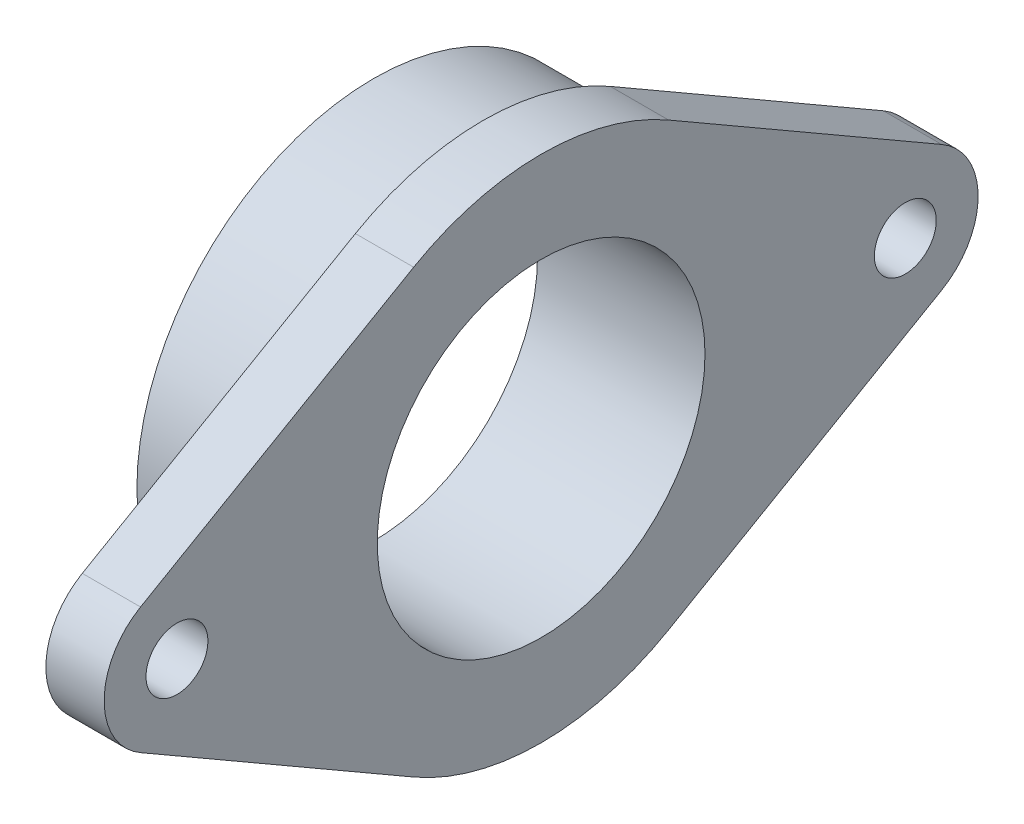
SolidWorks part; units mm, degrees
ref_plane "Front Plane" through (0, 0, 0) normal (0, 0, 1) x (1, 0, 0)
ref_plane "Top Plane" through (0, 0, 0) normal (0, 1, 0) x (1, 0, 0)
ref_plane "Right Plane" through (0, 0, 0) normal (1, 0, 0) x (0, 0, -1)
sketch "Sketch1" plane through (0, 0, 0) normal (1, 0, 0) x (0, 0, -1)
  circle A0 centre (0, 0) radius 32.5
  circle A1 centre (0, 0) radius 22.5
  dimension "D1" = 65
  dimension "D2" = 45
extrude "Boss-Extrude1" add sketch "Sketch1" along normal blind 15
sketch "Sketch2" plane through (15, 0, 0) normal (1, 0, 0) x (0, 0, -1)
  line L0 (-55, 8.6603) -> (-17.5, 30.3109)
  line L1 (-55, -8.6603) -> (-17.5, -30.3109)
  line L2 (55, 8.6603) -> (17.5, 30.3109)
  line L3 (55, -8.6603) -> (17.5, -30.3109)
  arc A0 (-17.5, -30.3109) -> (17.5, -30.3109) centre (0, 0) ccw
  arc A1 (55, -8.6603) -> (55, 8.6603) centre (50, 0) ccw
  arc A2 (-55, 8.6603) -> (-55, -8.6603) centre (-50, 0) ccw
  arc A3 (17.5, 30.3109) -> (-17.5, 30.3109) centre (0, 0) ccw
  circle A4 centre (0, 0) radius 22.5 construction
  circle A5 centre (0, 0) radius 22.5
  circle A6 centre (-50, 0) radius 4.25
  circle A7 centre (50, 0) radius 4.25
  dimension "D3" = 10
  dimension "D4" = 10
  dimension "D5" = 35
  dimension "D6" = 8.5
  dimension "D1" = 50
  dimension "D2" = 50
extrude "Boss-Extrude2" add sketch "Sketch2" along normal blind 8
